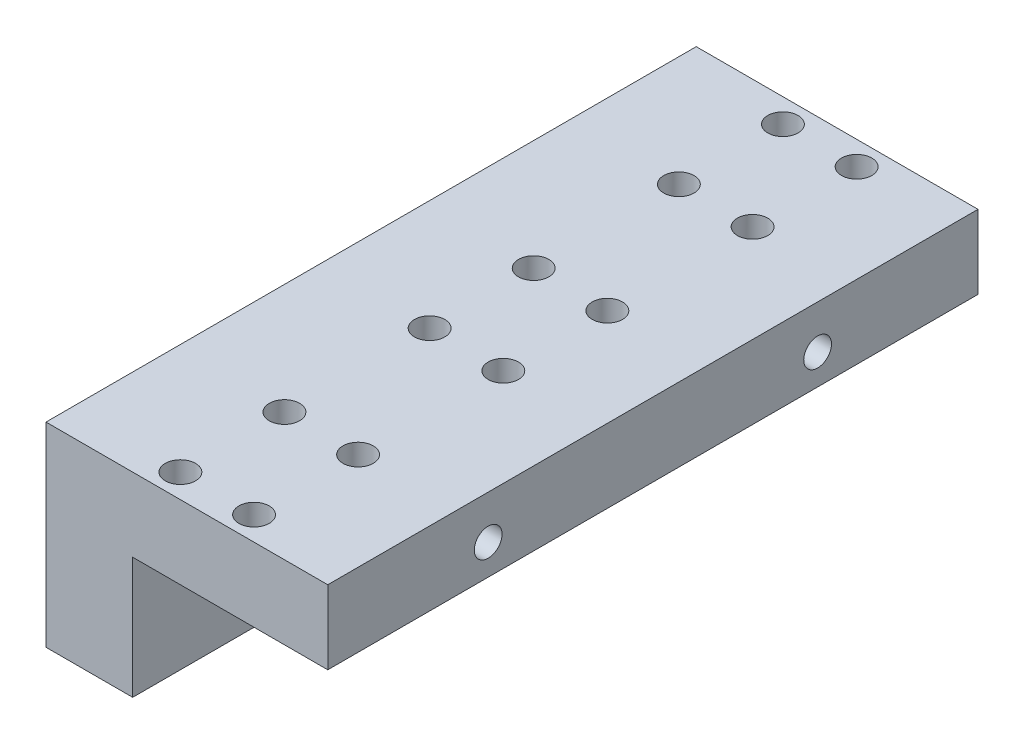
SolidWorks part; units mm, degrees
ref_plane "Front Plane" through (0, 0, 0) normal (0, 0, 1) x (1, 0, 0)
ref_plane "Top Plane" through (0, 0, 0) normal (0, 1, 0) x (1, 0, 0)
ref_plane "Right Plane" through (0, 0, 0) normal (1, 0, 0) x (0, 0, -1)
sketch "Sketch2" plane through (0, 0, 0) normal (0, 0, 1) x (1, 0, 0)
  line L0 (0, 0) -> (0, 45)
  line L1 (0, 45) -> (65, 45)
  line L2 (65, 45) -> (65, 28)
  line L3 (65, 28) -> (20, 28)
  line L4 (20, 28) -> (20, 0)
  line L5 (20, 0) -> (0, 0)
  dimension "D1" = 20
  dimension "D3" = 45
  dimension "D4" = 17
  dimension "D2" = 28
extrude "Boss-Extrude1" add sketch "Sketch2" along normal blind 150
sketch "Sketch3" plane through (0, 0, 0) normal (-1, 0, 0) x (0, 0, 1)
  line L0 (0, 19) -> (150, 19) construction
  line L1 (0, 45) -> (0, 0) construction
  line L2 (150, 45) -> (150, 0) construction
  line L3 (150, 13) -> (0, 13) construction
  line L4 (0, 35) -> (150, 35) construction
  line L5 (75, 45) -> (75, 0) construction
  line L6 (150, 45) -> (0, 45) construction
  line L7 (150, 0) -> (0, 0) construction
  circle A0 centre (17.5, 19) radius 4.25
  circle A1 centre (132.5, 19) radius 4.25
  circle A2 centre (75, 13) radius 4.25
  circle A3 centre (37, 35) radius 3.2
  circle A4 centre (113, 35) radius 3.2
  dimension "D1" = 8.5
  dimension "D2" = 8.5
  dimension "D7" = 8.5
  dimension "D9" = 6.4
  dimension "D10" = 6.4
  dimension "D3" = 57.5
  dimension "D4" = 57.5
  dimension "D5" = 19
  dimension "D6" = 13
  dimension "D8" = 35
  dimension "D11" = 38
  dimension "D12" = 38
extrude "Cut-Extrude1" cut sketch "Sketch3" against normal through all
sketch "Sketch4" plane through (0, 28, 0) normal (0, 1, 0) x (1, 0, 0)
  line L0 (48, -35) -> (48, 0) construction
  line L1 (48, 0) -> (20, 0) construction
  line L2 (20, 0) -> (20, -35) construction
  line L3 (20, -35) -> (48, -35) construction
  line L4 (48, -17.5) -> (20, -17.5) construction
  line L5 (34, -35) -> (34, 0) construction
  line L6 (25.5, 0) -> (25.5, -150) construction
  line L7 (0, -75) -> (65, -75) construction
  line L8 (20, 0) -> (65, 0) construction
  line L10 (20, -150) -> (65, -150) construction
  line L13 (20, -150) -> (20, 0) construction
  line L14 (0, -150) -> (0, 0) construction
  line L15 (65, 0) -> (0, 0) construction
  line L16 (65, -150) -> (65, 0) construction
  line L18 (48, -92.5) -> (48, -57.5) construction
  line L19 (48, -57.5) -> (20, -57.5) construction
  line L20 (20, -57.5) -> (20, -92.5) construction
  line L21 (20, -92.5) -> (48, -92.5) construction
  line L22 (48, -75) -> (20, -75) construction
  line L23 (34, -92.5) -> (34, -57.5) construction
  circle A28 centre (42.5, -29.5) radius 2
  circle A29 centre (42.5, -5.5) radius 2
  circle A30 centre (25.5, -5.5) radius 2
  circle A31 centre (25.5, -29.5) radius 2
  circle A32 centre (42.5, -144.5) radius 2
  circle A33 centre (42.5, -120.5) radius 2
  circle A34 centre (25.5, -120.5) radius 2
  circle A35 centre (25.5, -144.5) radius 2
  circle A36 centre (42.5, -87) radius 2
  circle A37 centre (42.5, -63) radius 2
  circle A38 centre (25.5, -63) radius 2
  circle A39 centre (25.5, -87) radius 2
  dimension "D10" = 8.5
  dimension "D11" = 12
  dimension "D12" = 12
  dimension "D13" = 8.5
  dimension "D5" = 4
  dimension "D6" = 4
  dimension "D7" = 4
  dimension "D8" = 4
  dimension "D21" = 4
  dimension "D22" = 4
  dimension "D23" = 8.5
  dimension "D24" = 8.5
  dimension "D19" = 4
  dimension "D20" = 4
  dimension "D2" = 28
  dimension "D3" = 28
  dimension "D4" = 35
  dimension "D9" = 8.5
  dimension "D14" = 8.5
  dimension "D15" = 12
  dimension "D16" = 12
  dimension "D17" = 5.5
  dimension "D25" = 12
  dimension "D26" = 12
  dimension "D27" = 8.5
  dimension "D28" = 8.5
  dimension "D29" = 12
  dimension "D18" = 35
  dimension "D30" = 12
extrude "Cut-Extrude2" cut sketch "Sketch4" along normal through all contours A29 | A30 | A31 | A28 | A35 | A32 | A34 | A33 | A39 | A36 | A38 | A37
sketch "Sketch5" plane through (0, 45, 0) normal (0, 1, 0) x (1, 0, 0)
  circle A0 centre (25.5, -5.5) radius 3.5
  circle A1 centre (42.5, -5.5) radius 3.5
  circle A2 centre (25.5, -29.5) radius 3.5
  circle A3 centre (42.5, -29.5) radius 3.5
  circle A4 centre (25.5, -63) radius 3.5
  circle A5 centre (42.5, -63) radius 3.5
  circle A6 centre (25.5, -87) radius 3.5
  circle A7 centre (42.5, -87) radius 3.5
  circle A8 centre (25.5, -120.5) radius 3.5
  circle A9 centre (42.5, -120.5) radius 3.5
  circle A10 centre (42.5, -144.5) radius 3.5
  circle A11 centre (25.5, -144.5) radius 3.5
  dimension "D1" = 7
extrude "Cut-Extrude3" cut sketch "Sketch5" against normal offset from surface (5 mm away) 5 up to face at (27.5, 45, 120.5)
equation "\"SyringeDiameter\"= 20"
equation "\"SyringeLength\"= 100"
equation "\"PlungerDiameter\"= 5"
equation "\"PlungerLength\"= 110"
equation "\"VSlotWidth\"= 30"
equation "\"VSlotDepth\"= 20"
equation "\"FingerFlangeDiameter\"= 30"
equation "\"VSlotBackPlateThickness\"= 5"
equation "\"GuideRodDiameter\"= 8.5"
equation "\"LeadScrewDiameter\"= 8.5"
equation "\"GuideRodSpacing\" = 16.25 + 4"
equation "\"LeadScrewSpacing\" = 10.25 + 4"
equation "\"ThreadedInsertDiameter\"= 7.1"
equation "\"ThreadedInsertDepth\"= 10"
equation "\"MountingHoleDiameter\"= 3"
equation "\"MountingHoleSpacing\"= 20"
equation "\"BlockHeight\" = 50"
equation "\"BlockWidth\"= \"RodToScrew\" * 2 + 30"
equation "\"BlockDepth\"= 20"
equation "\"VSlotAngle\"= 90"
equation "\"GuideRodSideWidth\"= 10"
equation "\"ScrewHeight\" = 35"
equation "\"ThreadedInsertSideWidth\" = 50"
equation "\"ScrewMountDistance\"= 25"
equation "\"RodtoRod\"= 115"
equation "\"RodToScrew\"= \"RodtoRod\" / 2"
equation "\"D1@Sketch2\"=\"BlockDepth\""
equation "\"D1@Boss-Extrude1\"=\"BlockWidth\""
equation "\"D1@Sketch3\"=\"GuideRodDiameter\""
equation "\"D2@Sketch3\"=\"GuideRodDiameter\""
equation "\"D3@Sketch3\"=\"RodToScrew\""
equation "\"D4@Sketch3\"=\"RodToScrew\""
equation "\"D7@Sketch3\"=\"LeadScrewDiameter\""
equation "\"D8@Sketch3\"=\"ScrewHeight\""
